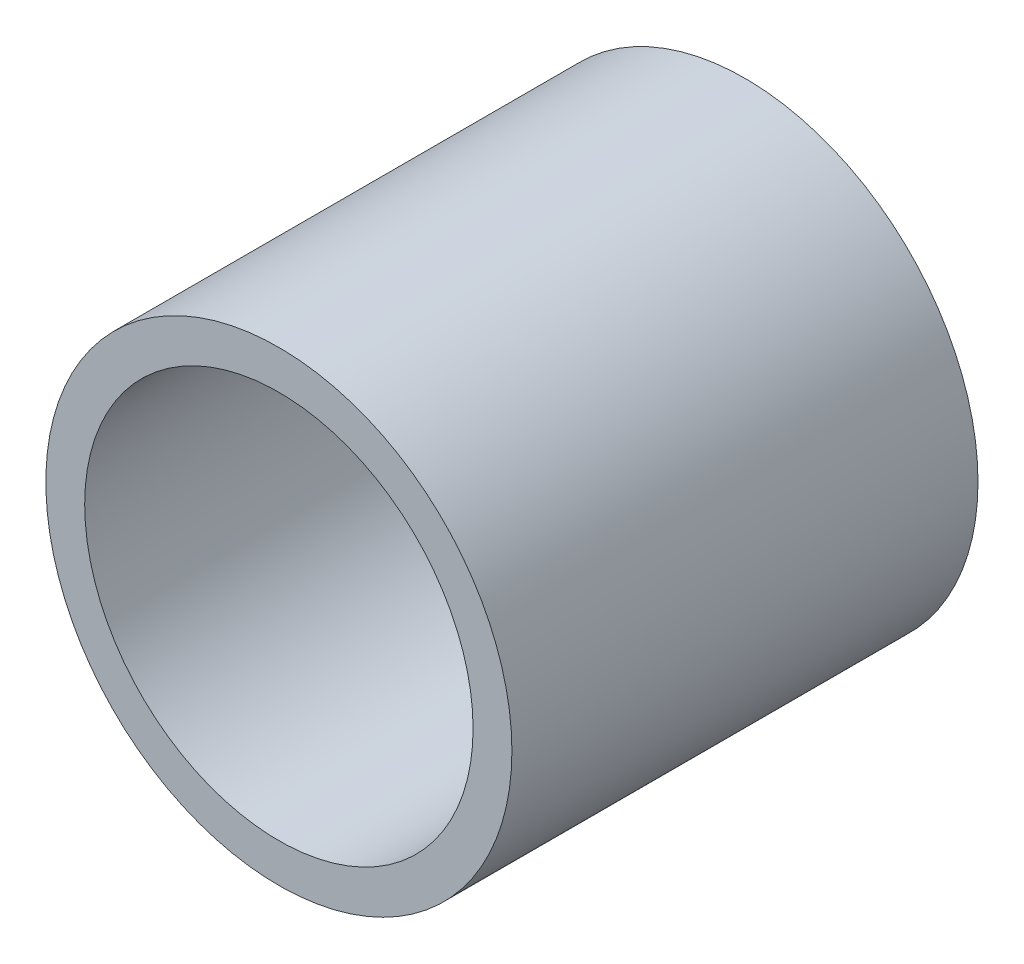
SolidWorks part; units mm, degrees
ref_plane "前视基准面" through (0, 0, 0) normal (0, 0, 1) x (1, 0, 0)
ref_plane "上视基准面" through (0, 0, 0) normal (0, 1, 0) x (1, 0, 0)
ref_plane "右视基准面" through (0, 0, 0) normal (1, 0, 0) x (0, 0, -1)
sketch "草图1" plane through (0, 0, 0) normal (0, 0, 1) x (1, 0, 0)
  circle A0 centre (0, 0) radius 6
  circle A1 centre (0, 0) radius 5
  dimension "D1" = 10
  dimension "D2" = 12
extrude "凸台-拉伸1" add sketch "草图1" along normal blind 12
